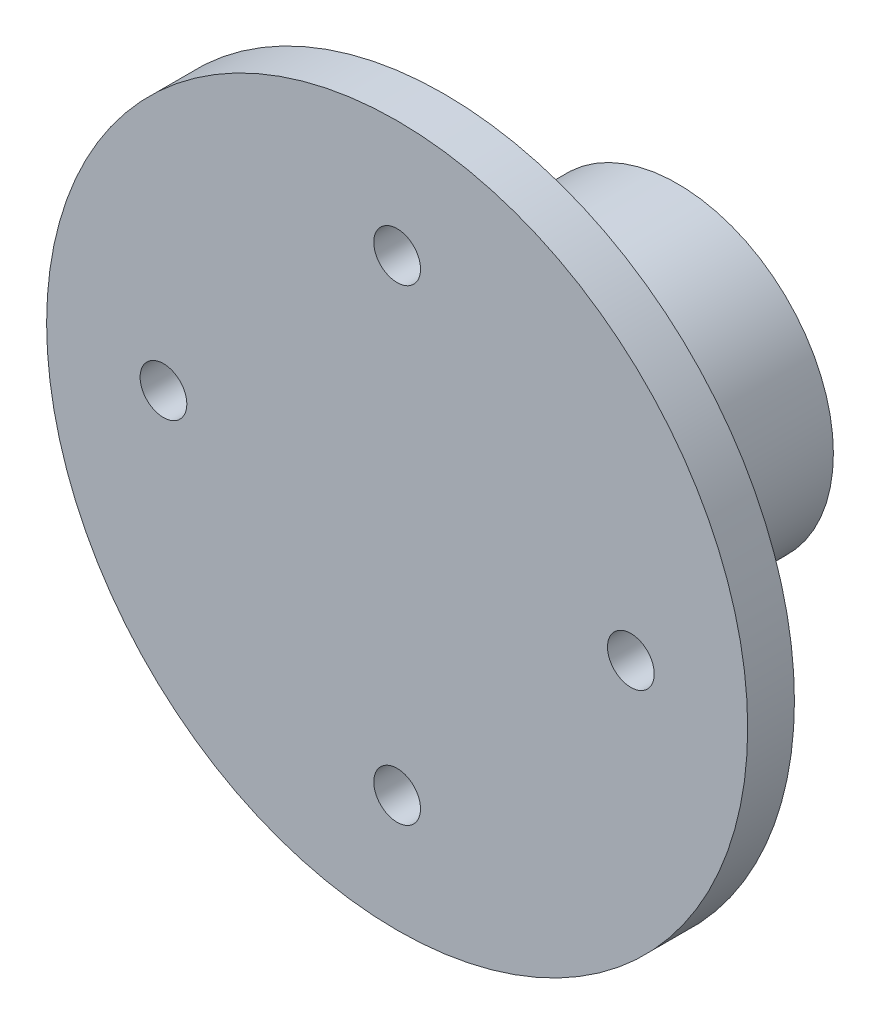
SolidWorks part; units mm, degrees
ref_plane "Front Plane" through (0, 0, 0) normal (0, 0, 1) x (1, 0, 0)
ref_plane "Top Plane" through (0, 0, 0) normal (0, 1, 0) x (1, 0, 0)
ref_plane "Right Plane" through (0, 0, 0) normal (1, 0, 0) x (0, 0, -1)
sketch "Sketch1" plane through (0, 0, 0) normal (0, 0, 1) x (1, 0, 0)
  circle A0 centre (0, 10) radius 15
  circle A1 centre (0, 25) radius 1.5
  circle A2 centre (15, 10) radius 1.5
  circle A3 centre (0, -5) radius 1.5
  circle A4 centre (-15, 10) radius 1.5
  point P14 (0, 10)
  dimension "D1" = 30
  dimension "D3" = 3
  dimension "D4" = 4
sketch "Sketch2" plane through (0, 0, 0) normal (0, 0, 1) x (1, 0, 0)
  circle A0 centre (0, 10) radius 22.5
  dimension "D1" = 45
extrude "Boss-Extrude1" add sketch "Sketch2" along normal blind 3
sketch "Sketch3" plane through (0, 0, 0) normal (0, 0, -1) x (-1, 0, 0)
  circle A0 centre (0, 10) radius 10
  circle A1 centre (0, 10) radius 7
  dimension "D1" = 20
  dimension "D2" = 3
extrude "Boss-Extrude2" add sketch "Sketch3" along normal blind 15 contours A0 | A1
extrude "Cut-Extrude1" cut sketch "Sketch1" along normal blind 9 contours A4 | A3 | A2 | A1
